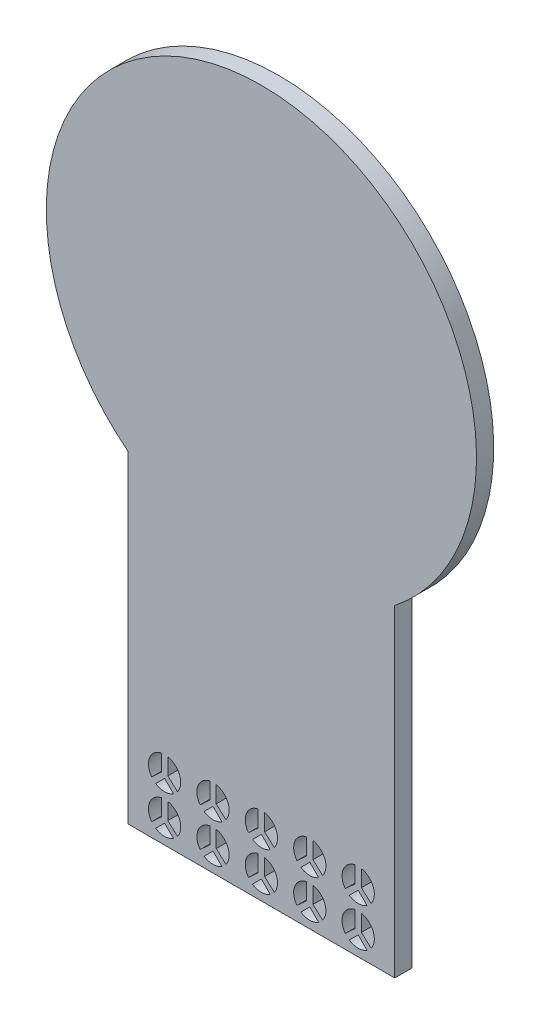
SolidWorks part; units mm, degrees
ref_plane "前视基准面" through (0, 0, 0) normal (0, 0, 1) x (1, 0, 0)
ref_plane "上视基准面" through (0, 0, 0) normal (0, 1, 0) x (1, 0, 0)
ref_plane "右视基准面" through (0, 0, 0) normal (1, 0, 0) x (0, 0, -1)
sketch "草图1" plane through (0, 0, 0) normal (0, 0, 1) x (1, 0, 0)
  line L8 (0, 0) -> (124, 0)
  line L9 (0, 0) -> (0, 150)
  line L11 (124, 0) -> (124, 150)
  line L12 (62, 0) -> (62, 339.3042) construction
  arc A4 (124, 150) -> (0, 150) centre (62, 228.4602) ccw
  point P5 (0, 0)
  point P7 (0, 0)
  dimension "D3" = 200
  dimension "D1" = 124
  dimension "D2" = 150
extrude "凸台-拉伸1" add sketch "草图1" along normal blind 8
sketch "草图2" plane through (0, 0, 8) normal (0, 0, 1) x (1, 0, 0)
  line L1 (38.0009, 18.335) -> (38.0009, 10.6146)
  line L2 (40.9991, 18.335) -> (40.9991, 10.6146)
  line L3 (38.0009, 10.6146) -> (33.5004, 6.4859)
  line L4 (40.9991, 10.6146) -> (45.4996, 6.4859)
  line L5 (43.6296, 4.7257) -> (39.4941, 8.8611)
  line L6 (39.4941, 8.8611) -> (35.3633, 4.7303)
  line L7 (60.5009, 18.335) -> (60.5009, 10.6146)
  line L8 (63.4991, 18.335) -> (63.4991, 10.6146)
  line L9 (60.5009, 10.6146) -> (56.0004, 6.4859)
  line L10 (63.4991, 10.6146) -> (67.9996, 6.4859)
  line L11 (66.1296, 4.7257) -> (61.9941, 8.8611)
  line L12 (61.9941, 8.8611) -> (57.8633, 4.7303)
  line L13 (83.0009, 18.335) -> (83.0009, 10.6146)
  line L14 (85.9991, 18.335) -> (85.9991, 10.6146)
  line L15 (83.0009, 10.6146) -> (78.5004, 6.4859)
  line L16 (85.9991, 10.6146) -> (90.4996, 6.4859)
  line L17 (88.6296, 4.7257) -> (84.4941, 8.8611)
  line L18 (84.4941, 8.8611) -> (80.3633, 4.7303)
  line L19 (105.5009, 18.335) -> (105.5009, 10.6146)
  line L20 (108.4991, 18.335) -> (108.4991, 10.6146)
  line L21 (105.5009, 10.6146) -> (101.0004, 6.4859)
  line L22 (108.4991, 10.6146) -> (112.9996, 6.4859)
  line L23 (111.1296, 4.7257) -> (106.9941, 8.8611)
  line L24 (106.9941, 8.8611) -> (102.8633, 4.7303)
  line L26 (38.0009, 36.335) -> (38.0009, 28.6146)
  line L27 (40.9991, 36.335) -> (40.9991, 28.6146)
  line L28 (38.0009, 28.6146) -> (33.5004, 24.4859)
  line L29 (40.9991, 28.6146) -> (45.4996, 24.4859)
  line L30 (15.5009, 18.335) -> (15.5009, 10.6146)
  line L31 (18.4991, 18.335) -> (18.4991, 10.6146)
  line L32 (15.5009, 10.6146) -> (11.0004, 6.4859)
  line L33 (18.4991, 10.6146) -> (22.9996, 6.4859)
  line L34 (21.1296, 4.7257) -> (16.9941, 8.8611)
  line L35 (16.9941, 8.8611) -> (12.8633, 4.7303)
  line L36 (43.6296, 22.7257) -> (39.4941, 26.8611)
  line L37 (39.4941, 26.8611) -> (35.3633, 22.7303)
  line L38 (60.5009, 36.335) -> (60.5009, 28.6146)
  line L39 (63.4991, 36.335) -> (63.4991, 28.6146)
  line L40 (60.5009, 28.6146) -> (56.0004, 24.4859)
  line L41 (63.4991, 28.6146) -> (67.9996, 24.4859)
  line L42 (66.1296, 22.7257) -> (61.9941, 26.8611)
  line L43 (61.9941, 26.8611) -> (57.8633, 22.7303)
  line L44 (83.0009, 36.335) -> (83.0009, 28.6146)
  line L45 (85.9991, 36.335) -> (85.9991, 28.6146)
  line L46 (83.0009, 28.6146) -> (78.5004, 24.4859)
  line L47 (85.9991, 28.6146) -> (90.4996, 24.4859)
  line L48 (88.6296, 22.7257) -> (84.4941, 26.8611)
  line L49 (84.4941, 26.8611) -> (80.3633, 22.7303)
  line L50 (105.5009, 36.335) -> (105.5009, 28.6146)
  line L51 (108.4991, 36.335) -> (108.4991, 28.6146)
  line L52 (105.5009, 28.6146) -> (101.0004, 24.4859)
  line L53 (108.4991, 28.6146) -> (112.9996, 24.4859)
  line L54 (111.1296, 22.7257) -> (106.9941, 26.8611)
  line L55 (106.9941, 26.8611) -> (102.8633, 22.7303)
  line L56 (15.5009, 36.335) -> (15.5009, 28.6146)
  line L57 (18.4991, 36.335) -> (18.4991, 28.6146)
  line L58 (15.5009, 28.6146) -> (11.0004, 24.4859)
  line L59 (18.4991, 28.6146) -> (22.9996, 24.4859)
  line L60 (21.1296, 22.7257) -> (16.9941, 26.8611)
  line L61 (16.9941, 26.8611) -> (12.8633, 22.7303)
  line L62 (0, 150) -> (0, 0) construction
  line L63 (124, 0) -> (124, 150) construction
  arc A5 (15.5009, 18.335) -> (11.0004, 6.4859) centre (17, 10.9864) ccw
  arc A10 (35.3633, 4.7303) -> (43.6296, 4.7257) centre (39.5, 10.9864) ccw
  arc A11 (57.8633, 4.7303) -> (66.1296, 4.7257) centre (62, 10.9864) ccw
  arc A12 (80.3633, 4.7303) -> (88.6296, 4.7257) centre (84.5, 10.9864) ccw
  arc A13 (102.8633, 4.7303) -> (111.1296, 4.7257) centre (107, 10.9864) ccw
  arc A14 (12.8633, 4.7303) -> (21.1296, 4.7257) centre (17, 10.9864) ccw
  arc A15 (22.9996, 6.4859) -> (18.4991, 18.335) centre (17, 10.9864) ccw
  arc A16 (38.0009, 18.335) -> (33.5004, 6.4859) centre (39.5, 10.9864) ccw
  arc A17 (45.4996, 6.4859) -> (40.9991, 18.335) centre (39.5, 10.9864) ccw
  arc A18 (60.5009, 18.335) -> (56.0004, 6.4859) centre (62, 10.9864) ccw
  arc A19 (67.9996, 6.4859) -> (63.4991, 18.335) centre (62, 10.9864) ccw
  arc A20 (83.0009, 18.335) -> (78.5004, 6.4859) centre (84.5, 10.9864) ccw
  arc A21 (90.4996, 6.4859) -> (85.9991, 18.335) centre (84.5, 10.9864) ccw
  arc A22 (105.5009, 18.335) -> (101.0004, 6.4859) centre (107, 10.9864) ccw
  arc A23 (112.9996, 6.4859) -> (108.4991, 18.335) centre (107, 10.9864) ccw
  arc A24 (15.5009, 36.335) -> (11.0004, 24.4859) centre (17, 28.9864) ccw
  arc A25 (35.3633, 22.7303) -> (43.6296, 22.7257) centre (39.5, 28.9864) ccw
  arc A26 (57.8633, 22.7303) -> (66.1296, 22.7257) centre (62, 28.9864) ccw
  arc A27 (80.3633, 22.7303) -> (88.6296, 22.7257) centre (84.5, 28.9864) ccw
  arc A28 (102.8633, 22.7303) -> (111.1296, 22.7257) centre (107, 28.9864) ccw
  arc A29 (12.8633, 22.7303) -> (21.1296, 22.7257) centre (17, 28.9864) ccw
  arc A30 (22.9996, 24.4859) -> (18.4991, 36.335) centre (17, 28.9864) ccw
  arc A31 (38.0009, 36.335) -> (33.5004, 24.4859) centre (39.5, 28.9864) ccw
  arc A32 (45.4996, 24.4859) -> (40.9991, 36.335) centre (39.5, 28.9864) ccw
  arc A33 (60.5009, 36.335) -> (56.0004, 24.4859) centre (62, 28.9864) ccw
  arc A34 (67.9996, 24.4859) -> (63.4991, 36.335) centre (62, 28.9864) ccw
  arc A35 (83.0009, 36.335) -> (78.5004, 24.4859) centre (84.5, 28.9864) ccw
  arc A36 (90.4996, 24.4859) -> (85.9991, 36.335) centre (84.5, 28.9864) ccw
  arc A37 (105.5009, 36.335) -> (101.0004, 24.4859) centre (107, 28.9864) ccw
  arc A38 (112.9996, 24.4859) -> (108.4991, 36.335) centre (107, 28.9864) ccw
  dimension "D1" = 17
  dimension "D3" = 17
  dimension "D2" = 5
  dimension "D4" = 2
extrude "切除-拉伸1" cut sketch "草图2" against normal blind 10
